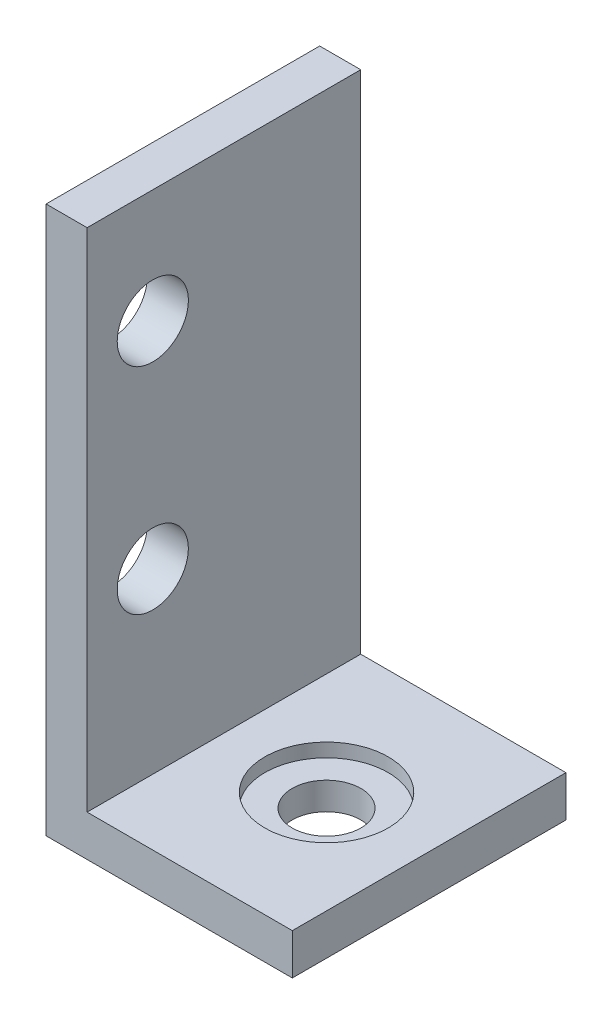
SolidWorks part; units mm, degrees
ref_plane "Front Plane" through (0, 0, 0) normal (0, 0, 1) x (1, 0, 0)
ref_plane "Top Plane" through (0, 0, 0) normal (0, 1, 0) x (1, 0, 0)
ref_plane "Right Plane" through (0, 0, 0) normal (1, 0, 0) x (0, 0, -1)
sketch "Sketch1" plane through (0, 0, 0) normal (0, 1, 0) x (1, 0, 0)
  line L0 (15.6259, 9.1151) -> (15.6259, 29.1151)
  line L1 (30.6259, 9.1151) -> (30.6259, 29.1151)
  line L2 (15.6259, 29.1151) -> (30.6259, 29.1151)
  line L3 (30.6259, 9.1151) -> (15.6259, 9.1151)
  circle A0 centre (23.1259, 19.1151) radius 2.51
  dimension "D1" = 15
extrude "Boss-Extrude1" add sketch "Sketch1" along normal blind 3
sketch "Sketch2" plane through (0, 3, 0) normal (0, 1, 0) x (1, 0, 0)
  circle A0 centre (23.1259, 19.1151) radius 4.51
extrude "Cut-Extrude1" cut sketch "Sketch2" against normal blind 1
sketch "Sketch3" plane through (0, 3, 0) normal (0, 1, 0) x (1, 0, 0)
  line L4 (15.6259, 29.1151) -> (15.6259, 9.1151)
  line L5 (12.6259, 29.1151) -> (12.6259, 9.1151)
  line L6 (12.6259, 29.1151) -> (15.6259, 29.1151)
  line L7 (12.6259, 9.1151) -> (15.6259, 9.1151)
  dimension "D1" = 3
extrude "Boss-Extrude2" add sketch "Sketch3" along normal blind 22 and the other way blind 3
sketch "Sketch4" plane through (12.6259, 0, 0) normal (-1, 0, 0) x (0, 0, 1)
  circle A0 centre (-23.1151, 19) radius 2.6
  circle A1 centre (-23.1151, 6) radius 2.6
extrude "Cut-Extrude2" cut sketch "Sketch4" against normal blind 22
sketch "Sketch5" plane through (15.6259, 0, 0) normal (1, 0, 0) x (0, 0, -1)
  circle A0 centre (23.1151, 19) radius 2.6
  circle A1 centre (23.1151, 6) radius 2.6
extrude "Boss-Extrude3" add sketch "Sketch5" against normal blind 3
ref_plane "Plane1" through (12.6259, 25, -29.1151) normal (0, 1, 0) x (1, 0, 0)
sketch "Sketch6" plane through (12.6259, 25, -29.1151) normal (0, 1, 0) x (1, 0, 0)
  line L0 (0, -14.8551) -> (0, -20)
  line L1 (0, 0) -> (0, -20) construction
  line L2 (0, -20) -> (3, -20)
  line L3 (3, -20) -> (3, -14.8551)
  line L4 (3, -20) -> (3, 0) construction
  line L6 (3, -14.8551) -> (3, 0)
  line L7 (3, 0) -> (0, 0)
  line L8 (0, 0) -> (0, -14.8551)
extrude "Cut-Extrude3" cut sketch "Sketch6" against normal blind 5
sketch "Sketch7" plane through (12.6259, 0, 0) normal (-1, 0, 0) x (0, 0, 1)
  line L0 (-9.1151, 20) -> (-29.1151, 20)
  line L1 (-29.1151, 20) -> (-29.1151, 40)
  line L2 (-29.1151, 40) -> (-9.1151, 40)
  line L3 (-9.1151, 40) -> (-9.1151, 20)
extrude "Boss-Extrude4" add sketch "Sketch7" against normal blind 3
sketch "Sketch8" plane through (15.6259, 0, 0) normal (1, 0, 0) x (0, 0, -1)
  circle A0 centre (13.9151, 16) radius 2.6
  circle A1 centre (13.9151, 26.1) radius 2.6
extrude "Cut-Extrude6" cut sketch "Sketch8" against normal blind 3
sketch "Sketch11" plane through (15.6259, 0, 0) normal (1, 0, 0) x (0, 0, -1)
  circle A0 centre (13.9151, 26.1) radius 2.6
extrude "Boss-Extrude6" add sketch "Sketch11" against normal blind 3
sketch "Sketch12" plane through (12.6259, 0, 0) normal (-1, 0, 0) x (0, 0, 1)
  circle A0 centre (-13.9151, 31.7) radius 2.6
extrude "Cut-Extrude7" cut sketch "Sketch12" against normal blind 3
sketch "Sketch9" plane through (15.6259, 0, 0) normal (1, 0, 0) x (0, 0, -1)
  circle A0 centre (13.9151, 16) radius 2.6
  circle A1 centre (13.9151, 26.1) radius 2.6
extrude "Boss-Extrude5" add sketch "Sketch9" against normal blind 3
